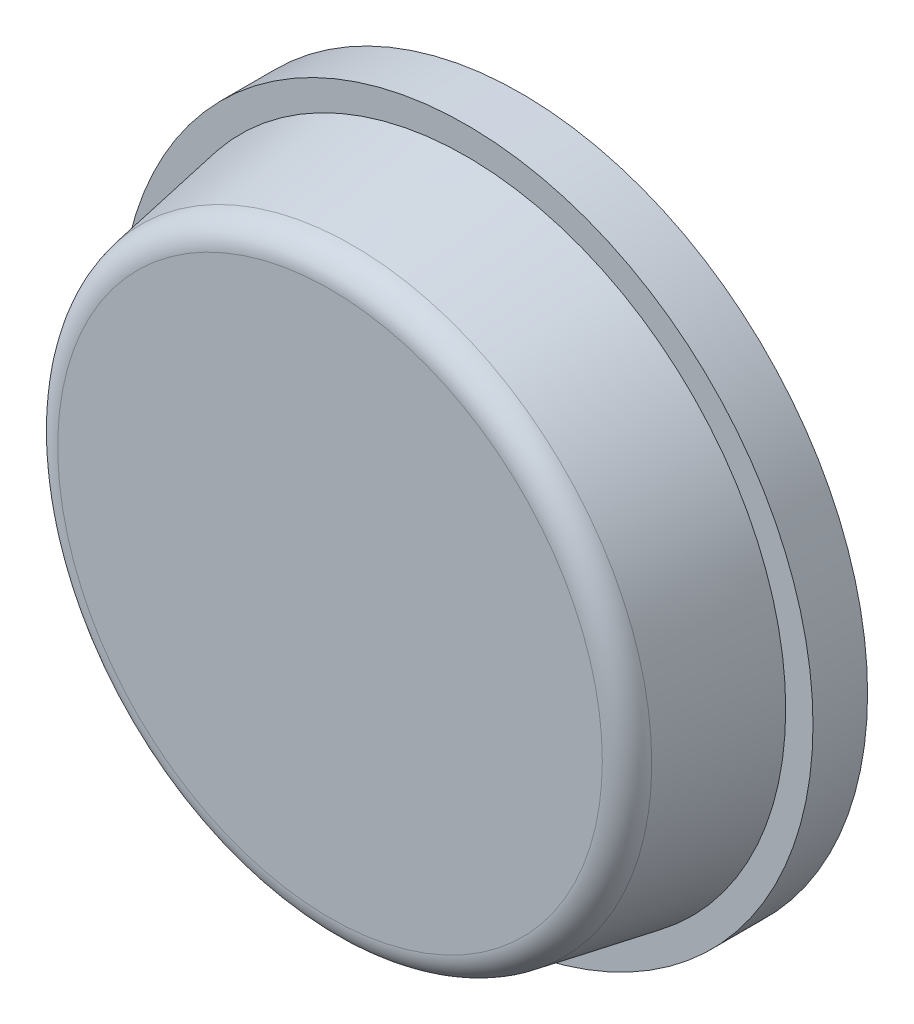
SolidWorks part; units mm, degrees
ref_plane "Plan de face" through (0, 0, 0) normal (0, 0, 1) x (1, 0, 0)
ref_plane "Plan de dessus" through (0, 0, 0) normal (0, 1, 0) x (1, 0, 0)
ref_plane "Plan de droite" through (0, 0, 0) normal (1, 0, 0) x (0, 0, -1)
sketch "Base" plane through (0, 0, 0) normal (0, 0, 1) x (1, 0, 0)
  circle A0 centre (0, 0) radius 6.35
  dimension "D1" = 12.7
extrude "Boss.-Extru.1_Base" add sketch "Base" along normal blind 1
sketch "Patin" plane through (0, 0, 1) normal (0, 0, 1) x (1, 0, 0)
  circle A0 centre (0, 0) radius 5.85
  dimension "D1" = 11.7
extrude "Boss.-Extru.2_Patin" add sketch "Patin" along normal blind 2.5 draft 10
fillet "Congé1_0.5mm_Patin" radius 0.5 1 edges at (5.4092, 0, 3.5)
sketch "Esquisse4" plane through (0, 0, 0) normal (0, 0, -1) x (-1, 0, 0)
  circle A0 centre (0, 0) radius 4 construction
  dimension "D1" = 8
